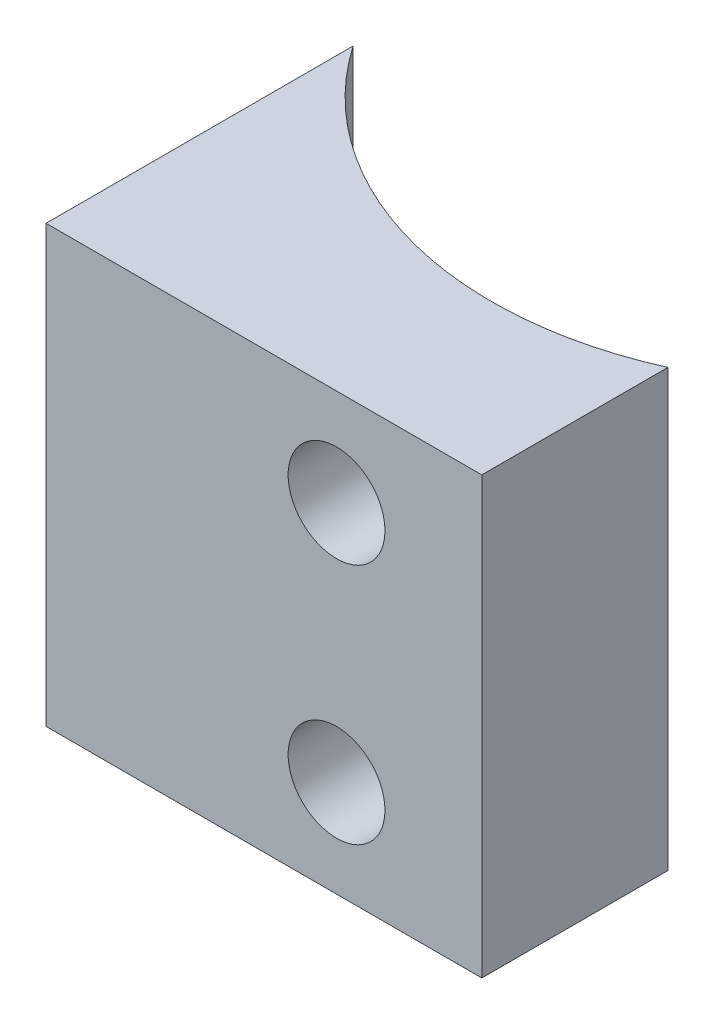
SolidWorks part; units mm, degrees
ref_plane "Front Plane" through (0, 0, 0) normal (0, 0, 1) x (1, 0, 0)
ref_plane "Top Plane" through (0, 0, 0) normal (0, 1, 0) x (1, 0, 0)
ref_plane "Right Plane" through (0, 0, 0) normal (1, 0, 0) x (0, 0, -1)
sketch "Sketch1" plane through (0, 0, 0) normal (0, 1, 0) x (1, 0, 0)
  line L1 (-30, -20) -> (15, -20)
  line L2 (-30, -20) -> (-30, -52.5)
  line L3 (-30, -52.5) -> (15, -52.5)
  line L4 (15, -20) -> (15, -52.5)
  circle A0 centre (0, 0) radius 36.5
  dimension "D1" = 73
  dimension "D2" = 52.5
  dimension "D3" = 45
  dimension "D4" = 15
  dimension "D5" = 32.5
extrude "Boss-Extrude1" add sketch "Sketch1" along normal blind 15 and the other way blind 30 contours A0 L1 L2 L3 L4
sketch "Sketch2" plane through (0, 0, 52.5) normal (0, 0, 1) x (1, 0, 0)
  line L0 (-30, 15) -> (15, 15) construction
  circle A0 centre (0, -20) radius 5
  circle A1 centre (0, 5) radius 5
  dimension "D1" = 10
  dimension "D2" = 10
  dimension "D3" = 25
  dimension "D4" = 10
extrude "Cut-Extrude1" cut sketch "Sketch2" against normal through all
